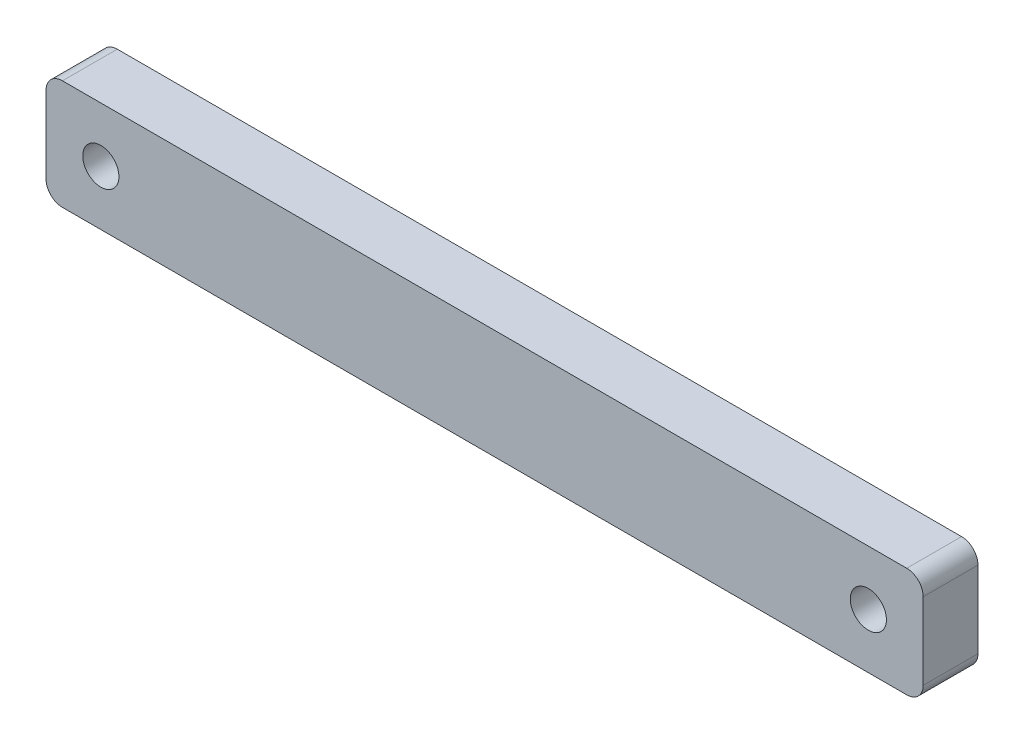
SolidWorks part; units mm, degrees
ref_plane "Front Plane" through (0, 0, 0) normal (0, 0, 1) x (1, 0, 0)
ref_plane "Top Plane" through (0, 0, 0) normal (0, 1, 0) x (1, 0, 0)
ref_plane "Right Plane" through (0, 0, 0) normal (1, 0, 0) x (0, 0, -1)
sketch "Sketch1" plane through (0, 0, 0) normal (0, 0, 1) x (1, 0, 0)
  line L1 (97.79, -12.7) -> (-97.79, -12.7)
  line L2 (101.6, -8.89) -> (101.6, 8.89)
  line L3 (97.79, 12.7) -> (-97.79, 12.7)
  line L4 (-101.6, -8.89) -> (-101.6, 8.89)
  line L5 (101.6, -12.7) -> (-101.6, 12.7) construction
  line L6 (101.6, 12.7) -> (-101.6, -12.7) construction
  arc A0 (101.6, 8.89) -> (97.79, 12.7) centre (97.79, 8.89) ccw
  arc A1 (97.79, -12.7) -> (101.6, -8.89) centre (97.79, -8.89) ccw
  arc A2 (-97.79, -12.7) -> (-101.6, -8.89) centre (-97.79, -8.89) cw
  arc A3 (-97.79, 12.7) -> (-101.6, 8.89) centre (-97.79, 8.89) ccw
  circle A4 centre (-88.9, 0) radius 4.191
  circle A5 centre (88.9, 0) radius 4.191
  point P0 (0, 0)
  dimension "D3" = 3.81
  dimension "D6" = 8.382
  dimension "D7" = 8.382
  dimension "D1" = 25.4
  dimension "D2" = 203.2
  dimension "D4" = 88.9
  dimension "D5" = 88.9
extrude "Boss-Extrude1" add sketch "Sketch1" along normal blind 12.7
sketch "Sketch2" plane through (0, 0, 0) normal (0, 0, -1) x (-1, 0, 0)
  circle A0 centre (-88.9, 0) radius 3.683
  circle A1 centre (88.9, 0) radius 3.683
extrude "Boss-Extrude2" add sketch "Sketch2" against normal blind 6.35
